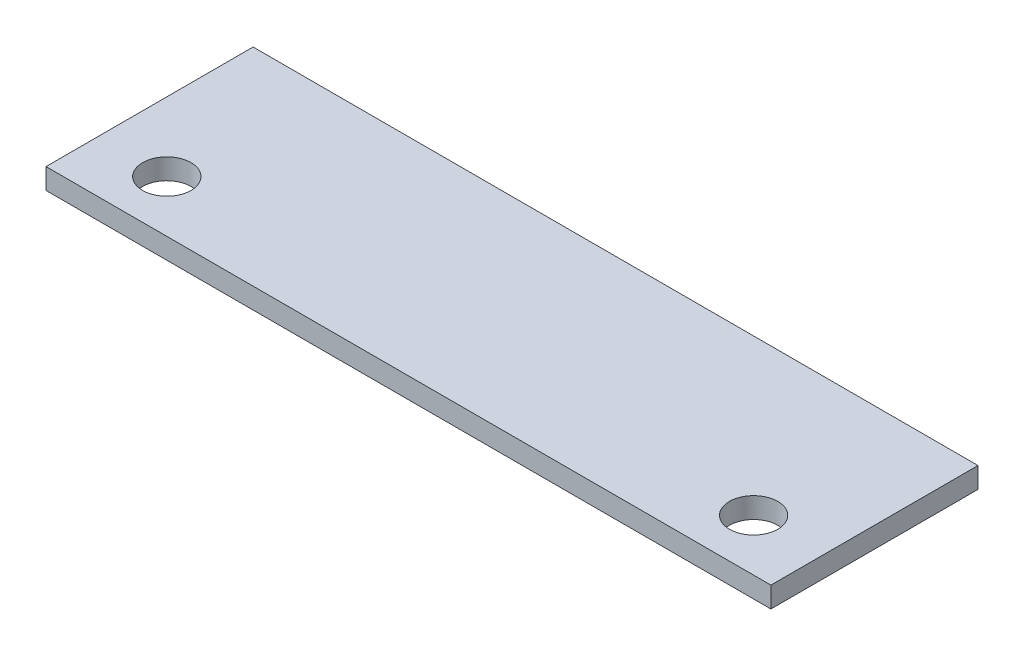
SolidWorks part; units mm, degrees
material "ASTM A36 Steel"
ref_plane "Front Plane" through (0, 0, 0) normal (0, 0, 1) x (1, 0, 0)
ref_plane "Top Plane" through (0, 0, 0) normal (0, 1, 0) x (1, 0, 0)
ref_plane "Right Plane" through (0, 0, 0) normal (1, 0, 0) x (0, 0, -1)
sketch "Sketch1" plane through (0, 0, 0) normal (0, 1, 0) x (1, 0, 0)
  line L1 (-105, -30) -> (105, -30)
  line L2 (-105, -30) -> (-105, 30)
  line L3 (-105, 30) -> (105, 30)
  line L4 (105, -30) -> (105, 30)
  line L5 (-105, -30) -> (105, 30) construction
  line L6 (-105, 30) -> (105, -30) construction
  point P0 (0, 0)
  dimension "D1" = 210
  dimension "D2" = 60
extrude "Boss-Extrude1" add sketch "Sketch1" along normal blind 6
sketch "Sketch2" plane through (0, 6, 0) normal (0, 1, 0) x (1, 0, 0)
  line L0 (-105, -30) -> (105, -30) construction
  line L1 (105, -30) -> (105, 30) construction
  line L2 (-105, 30) -> (-105, -30) construction
  circle A0 centre (85, -15) radius 7
  circle A1 centre (-85, -15) radius 7
  dimension "D1" = 14
  dimension "D2" = 15
  dimension "D3" = 20
  dimension "D4" = 14
  dimension "D5" = 20
  dimension "D6" = 15
extrude "Cut-Extrude1" cut sketch "Sketch2" against normal through all both and the other way through all
